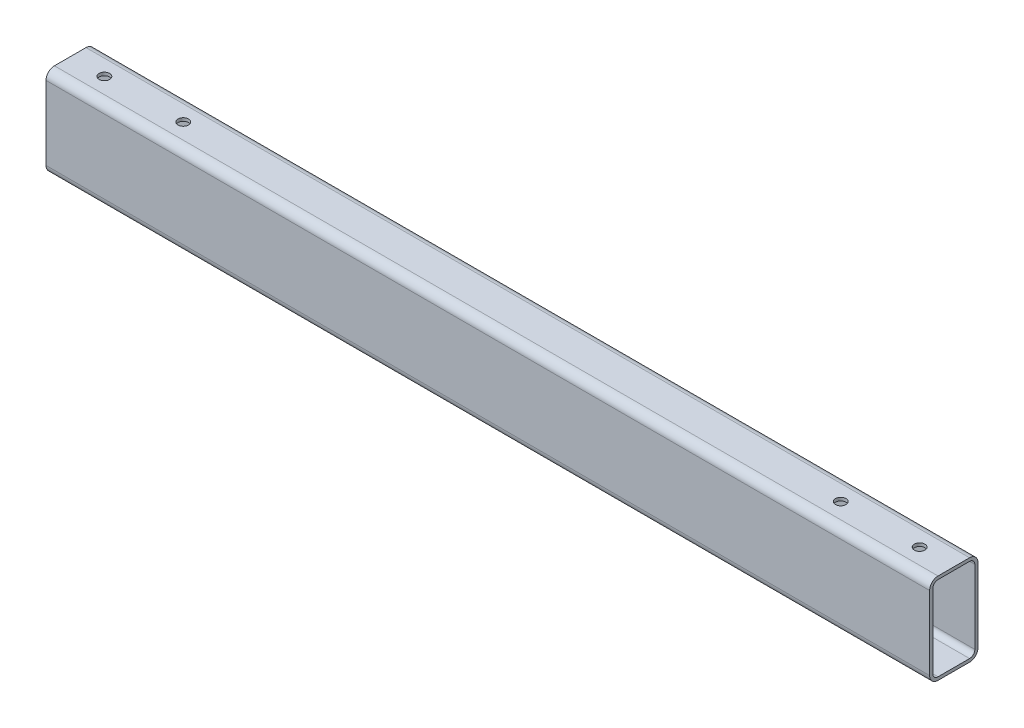
SolidWorks part; units mm, degrees
ref_plane "Front Plane" through (0, 0, 0) normal (0, 0, 1) x (1, 0, 0)
ref_plane "Top Plane" through (0, 0, 0) normal (0, 1, 0) x (1, 0, 0)
ref_plane "Right Plane" through (0, 0, 0) normal (1, 0, 0) x (0, 0, -1)
sketch "Sketch1" plane through (0, 0, 0) normal (1, 0, 0) x (0, 0, -1)
  line L1 (-15, -40) -> (15, -40)
  line L2 (-20, -35) -> (-20, 35)
  line L3 (-15, 40) -> (15, 40)
  line L4 (20, -35) -> (20, 35)
  line L5 (-20, -40) -> (20, 40) construction
  line L6 (-20, 40) -> (20, -40) construction
  arc A0 (-20, -35) -> (-15, -40) centre (-15, -35) ccw
  arc A1 (15, -40) -> (20, -35) centre (15, -35) ccw
  arc A2 (20, 35) -> (15, 40) centre (15, 35) ccw
  arc A3 (-15, 40) -> (-20, 35) centre (-15, 35) ccw
  point P0 (0, 0)
  dimension "D3" = 5
  dimension "D1" = 40
  dimension "D2" = 80
extrude "Extrude-Thin1" add sketch "Sketch1" along normal blind 420 and the other way blind 420 thin
sketch "Sketch3" plane through (0, 0, 0) normal (0, 1, 0) x (1, 0, 0)
  line L0 (0, -25.3) -> (0, 25.3) construction
  circle A0 centre (-387.5, 0) radius 5
  circle A1 centre (-312.5, 0) radius 5
  circle A2 centre (387.5, 0) radius 5
  circle A3 centre (312.5, 0) radius 5
  dimension "D1" = 10
  dimension "D2" = 312.5
  dimension "D3" = 75
extrude "Cut-Extrude1" cut sketch "Sketch3" against normal through all both and the other way through all
